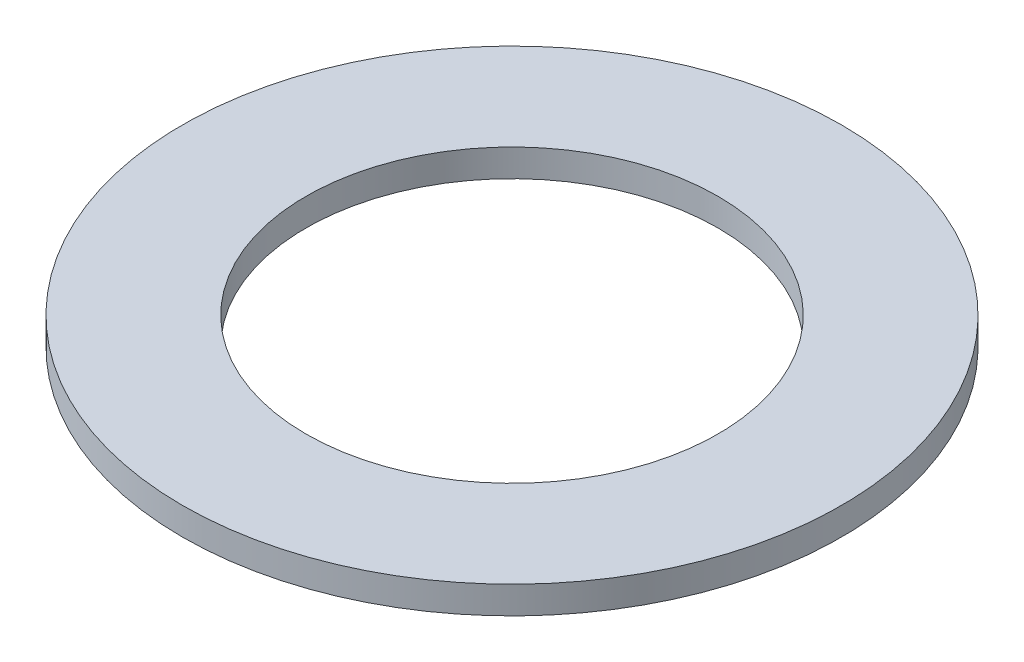
SolidWorks part; units mm, degrees
ref_plane "Alzado" through (0, 0, 0) normal (0, 0, 1) x (1, 0, 0)
ref_plane "Planta" through (0, 0, 0) normal (0, 1, 0) x (1, 0, 0)
ref_plane "Vista lateral" through (0, 0, 0) normal (1, 0, 0) x (0, 0, -1)
sketch "Croquis1" plane through (0, 0, 0) normal (0, 1, 0) x (1, 0, 0)
  circle A0 centre (0, 0) radius 6
  circle A1 centre (0, 0) radius 3.75
extrude "Saliente-Extruir1" add sketch "Croquis1" along normal blind 0.5
